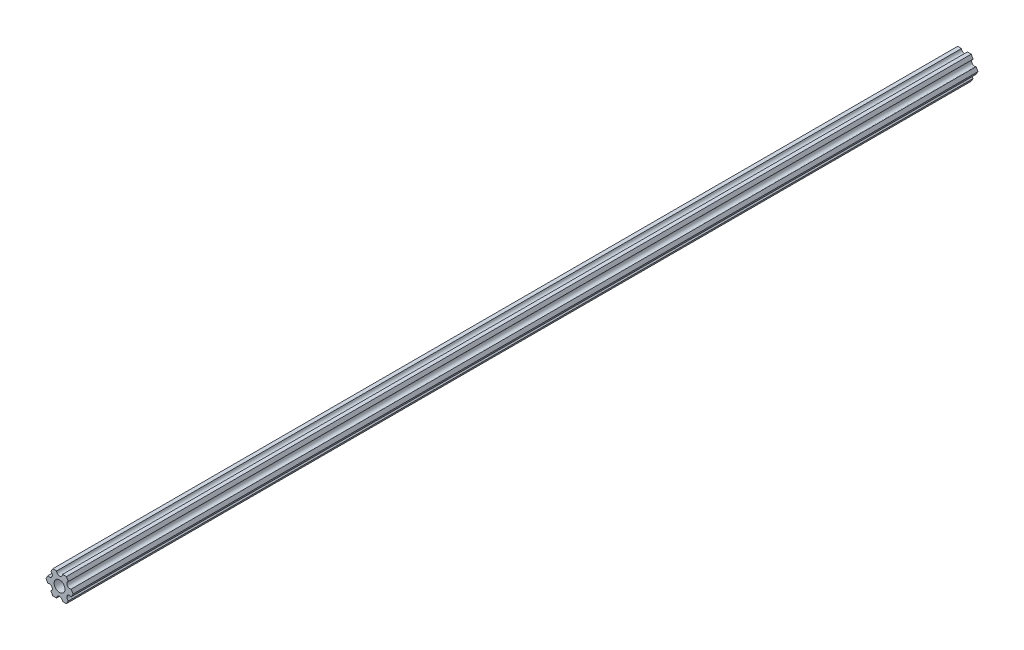
SolidWorks part; units mm, degrees
ref_plane "Front Plane" through (0, 0, 0) normal (0, 0, 1) x (1, 0, 0)
ref_plane "Top Plane" through (0, 0, 0) normal (0, 1, 0) x (1, 0, 0)
ref_plane "Right Plane" through (0, 0, 0) normal (1, 0, 0) x (0, 0, -1)
sketch "Sketch1" plane through (0, 0, 0) normal (0, 0, 1) x (1, 0, 0)
  line L0 (-1.5875, 6.35) -> (-3.6662, 6.35)
  line L1 (7.3323, 0) -> (6.293, 1.8002)
  line L2 (3.6662, 6.35) -> (1.5875, 6.35)
  line L3 (-3.6662, 6.35) -> (-4.7055, 4.5498)
  line L4 (-7.3323, 0) -> (-6.293, -1.8002)
  line L5 (-3.6662, -6.35) -> (-1.5875, -6.35)
  line L6 (3.6662, -6.35) -> (4.7055, -4.5498)
  line L7 (-6.293, 1.8002) -> (-7.3323, 0)
  line L8 (-4.7055, -4.5498) -> (-3.6662, -6.35)
  line L9 (1.5875, -6.35) -> (3.6662, -6.35)
  line L10 (6.293, -1.8002) -> (7.3323, 0)
  line L11 (4.7055, 4.5498) -> (3.6662, 6.35)
  circle A0 centre (0, 0) radius 2.9337
  arc A2 (-1.5875, 6.35) -> (1.5875, 6.35) centre (0, 6.35) ccw
  arc A3 (4.7055, 4.5498) -> (6.293, 1.8002) centre (5.4993, 3.175) ccw
  arc A4 (6.293, -1.8002) -> (4.7055, -4.5498) centre (5.4993, -3.175) ccw
  arc A5 (1.5875, -6.35) -> (-1.5875, -6.35) centre (0, -6.35) ccw
  arc A6 (-4.7055, -4.5498) -> (-6.293, -1.8002) centre (-5.4993, -3.175) ccw
  arc A7 (-6.293, 1.8002) -> (-4.7055, 4.5498) centre (-5.4993, 3.175) ccw
  dimension "D1" = 5.8674
  dimension "D3" = 3.175
  dimension "D4" = 6
extrude "Boss-Extrude1" add sketch "Sketch1" along normal mid plane 488.95
